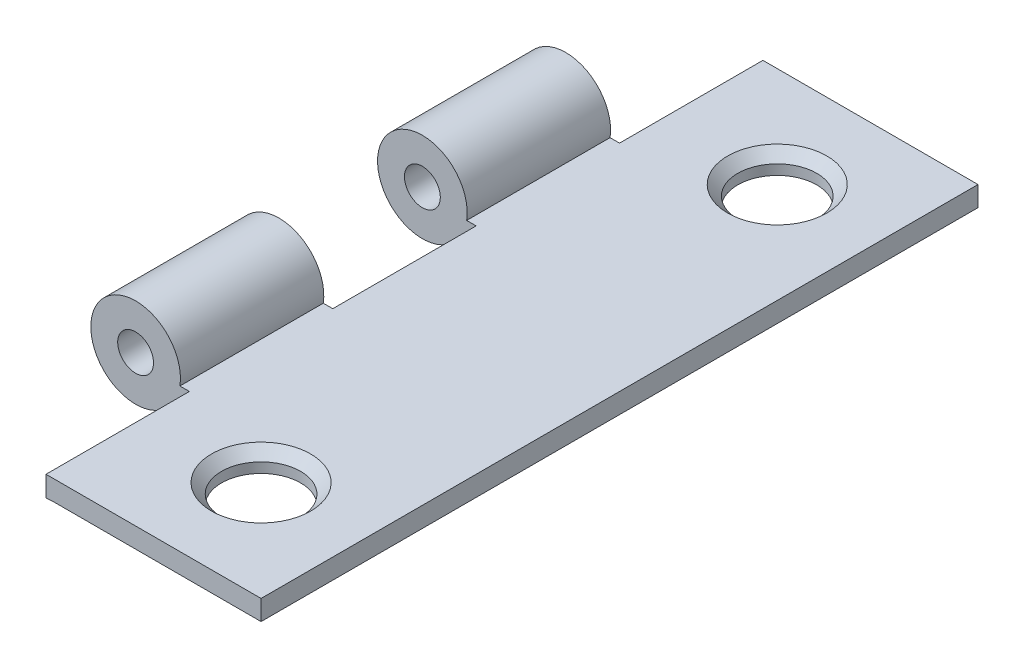
SolidWorks part; units mm, degrees
ref_plane "Front Plane" through (0, 0, 0) normal (0, 0, 1) x (1, 0, 0)
ref_plane "Top Plane" through (0, 0, 0) normal (0, 1, 0) x (1, 0, 0)
ref_plane "Right Plane" through (0, 0, 0) normal (1, 0, 0) x (0, 0, -1)
sketch "Sketch4" plane through (0, 0, 0) normal (0, 0, 1) x (1, 0, 0)
  line L0 (19.05, -0.4826) -> (3.1381, -0.4826)
  line L1 (19.05, -1.905) -> (2.54, -1.905)
  line L2 (19.05, -1.905) -> (19.05, -0.4826)
  circle A0 centre (0, 0) radius 3.175
  dimension "D1" = 6.35
  dimension "D2" = 15.9119
  dimension "D3" = 1.27
  dimension "D4" = 1.4224
extrude "Boss-Extrude2" add sketch "Sketch4" along normal mid plane 50.8 contours A0 | A0 L1 L2 L0
fillet "Fillet1" radius 5.08 1 edges at (2.54, -1.905, 0)
hole_wizard "M5 Clearance Hole1" positions "Sketch6" profile "Sketch7" hole size "M5" standard "ANSI Metric" end condition up to next
sketch "Sketch6" plane through (0, -0.4826, 0) normal (0, 1, 0) x (1, 0, 0)
  line L0 (19.05, -25.4) -> (19.05, 25.4) construction
  point P0 (11.938, 18.288)
  point P2 (11.938, -18.288)
  dimension "D1" = 18.288
  dimension "D2" = 18.288
  dimension "D3" = 7.112
sketch "Sketch7" plane through (11.938, -0.4826, -18.288) normal (1, 0, 0) x (0, 0, 1)
  line L0 (0, 0) -> (0, 1.4224)
  line L1 (0, 1.4224) -> (2.8, 1.4224)
  line L2 (2.8, 1.4224) -> (2.8, 0)
  line L5 (2.8, 0) -> (0, 0)
  line L11 (0, -6.35) -> (0, 107.95) construction
  dimension "Thru Hole Dia." = 5.6
  dimension "Thru Hole Depth" = 1.4224
sketch "Sketch9" plane through (0, 0, 0) normal (0, 1, 0) x (1, 0, 0)
  line L0 (-3.175, 25.4) -> (-3.175, -25.4)
  line L1 (3.81, -25.4) -> (-3.175, -25.4)
  line L2 (3.81, 25.4) -> (3.81, -25.4)
  line L3 (19.05, 25.4) -> (3.1381, 25.4) construction
  line L4 (19.05, -25.4) -> (3.1381, -25.4) construction
  line L5 (3.175, -25.4) -> (3.175, 25.4) construction
  line L6 (-3.175, 25.4) -> (3.81, 25.4)
  line L7 (-3.175, 15.24) -> (3.81, 15.24)
  line L8 (-3.175, 5.08) -> (3.81, 5.08)
  line L9 (-3.175, -5.08) -> (3.81, -5.08)
  line L10 (-3.175, -15.24) -> (3.81, -15.24)
  point P4 (-3.175, 15.24)
  point P5 (-3.175, 5.08)
  point P6 (-3.175, -5.08)
  point P7 (-3.175, -15.24)
  dimension "D1" = 0.635
extrude "Cut-Extrude1" cut sketch "Sketch9" against normal through all both and the other way through all contours L10 L0 L1 L2 | L0 L9 L2 L8 | L0 L7 L2 L6
sketch "Sketch10" plane through (0, 0, 25.4) normal (0, 0, 1) x (1, 0, 0)
  circle A0 centre (0, 0) radius 1.27
  dimension "D1" = 2.54
extrude "Cut-Extrude2" cut sketch "Sketch10" against normal through all
chamfer "Chamfer1" distance 0.7112 angle 45 2 edges at (11.938, -0.4826, -15.488) (11.938, -0.4826, 21.088)
equation "\"D2@Sketch6\"=\"D1@Sketch6\""
